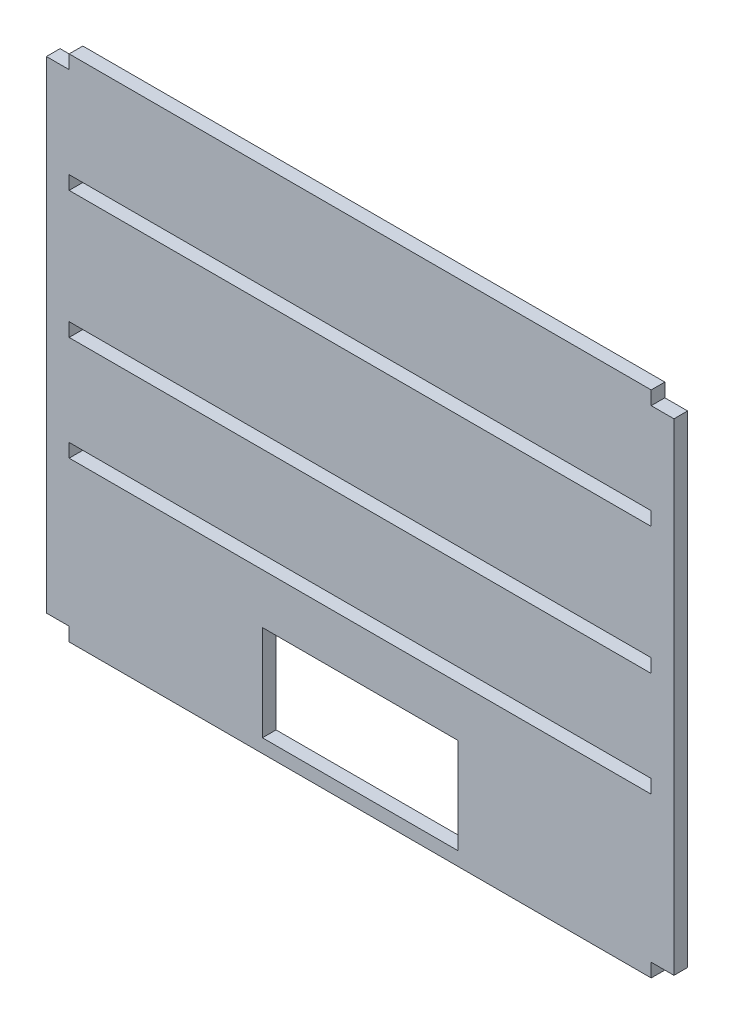
SolidWorks part; units mm, degrees
ref_plane "Front Plane" through (0, 0, 0) normal (0, 0, 1) x (1, 0, 0)
ref_plane "Top Plane" through (0, 0, 0) normal (0, 1, 0) x (1, 0, 0)
ref_plane "Right Plane" through (0, 0, 0) normal (1, 0, 0) x (0, 0, -1)
sketch "Sketch1" plane through (0, 0, 0) normal (0, 0, 1) x (1, 0, 0)
  line L0 (-95, 20.7939) -> (33, 20.7939)
  line L5 (38, -17.2061) -> (-100, -17.2061)
  line L6 (38, -17.2061) -> (38, 94.7939)
  line L7 (38, 94.7939) -> (-100, 94.7939)
  line L8 (-100, -17.2061) -> (-100, 94.7939)
  line L15 (-100, 91.7939) -> (-95, 91.7939)
  line L16 (-95, 94.7939) -> (-95, 91.7939)
  line L17 (-95, 20.7939) -> (-95, 17.7939)
  line L18 (38, 91.7939) -> (33, 91.7939)
  line L19 (33, 94.7939) -> (33, 91.7939)
  line L23 (33, -17.2061) -> (33, -14.2061)
  line L24 (38, -14.2061) -> (33, -14.2061)
  line L26 (-100, -14.2061) -> (-95, -14.2061)
  line L27 (-95, -17.2061) -> (-95, -14.2061)
  line L30 (-95, 43.7939) -> (33, 43.7939)
  line L31 (-95, 71.7939) -> (33, 71.7939)
  line L32 (-95, 71.7939) -> (-95, 68.7939)
  line L33 (-95, 68.7939) -> (33, 68.7939)
  line L34 (33, 71.7939) -> (33, 68.7939)
  line L35 (-95, 43.7939) -> (-95, 40.7939)
  line L36 (-95, 40.7939) -> (33, 40.7939)
  line L37 (33, 43.7939) -> (33, 40.7939)
  line L38 (-95, 17.7939) -> (33, 17.7939)
  line L39 (33, 20.7939) -> (33, 17.7939)
  line L41 (-52.5, 6.7939) -> (-9.5, 6.7939)
  line L42 (-52.5, 6.7939) -> (-52.5, -14.2061)
  line L43 (-52.5, -14.2061) -> (-9.5, -14.2061)
  line L44 (-9.5, 6.7939) -> (-9.5, -14.2061)
  point P0 (0, 0)
  point P30 (-95, 19.2939)
  point P35 (33, -15.7061)
  dimension "D1" = 138
  dimension "D2" = 112
  dimension "D3" = 5
  dimension "D4" = 3
  dimension "D5" = 3
  dimension "D6" = 20
  dimension "D7" = 128
  dimension "D8" = 5
  dimension "D9" = 25
  dimension "D10" = 5
  dimension "D11" = 5
  dimension "D12" = 20
  dimension "D13" = 5
  dimension "D14" = 5
  dimension "D15" = 3
  dimension "D16" = 43
  dimension "D17" = 21
  dimension "D18" = 3
  dimension "D19" = 42.5
  dimension "D20" = 42.5
  dimension "D21" = 3
  dimension "D22" = 3
  dimension "D23" = 11
extrude "Boss-Extrude2" add sketch "Sketch1" along normal blind 3 contours L27 L5 L23 L24 L6 L18 L19 L7 L16 L15 L8 L26 L31 L34 L33 L32 L30 L37 L36 L35 L0 L39 L38 L17 L41 L44 L43 L42
